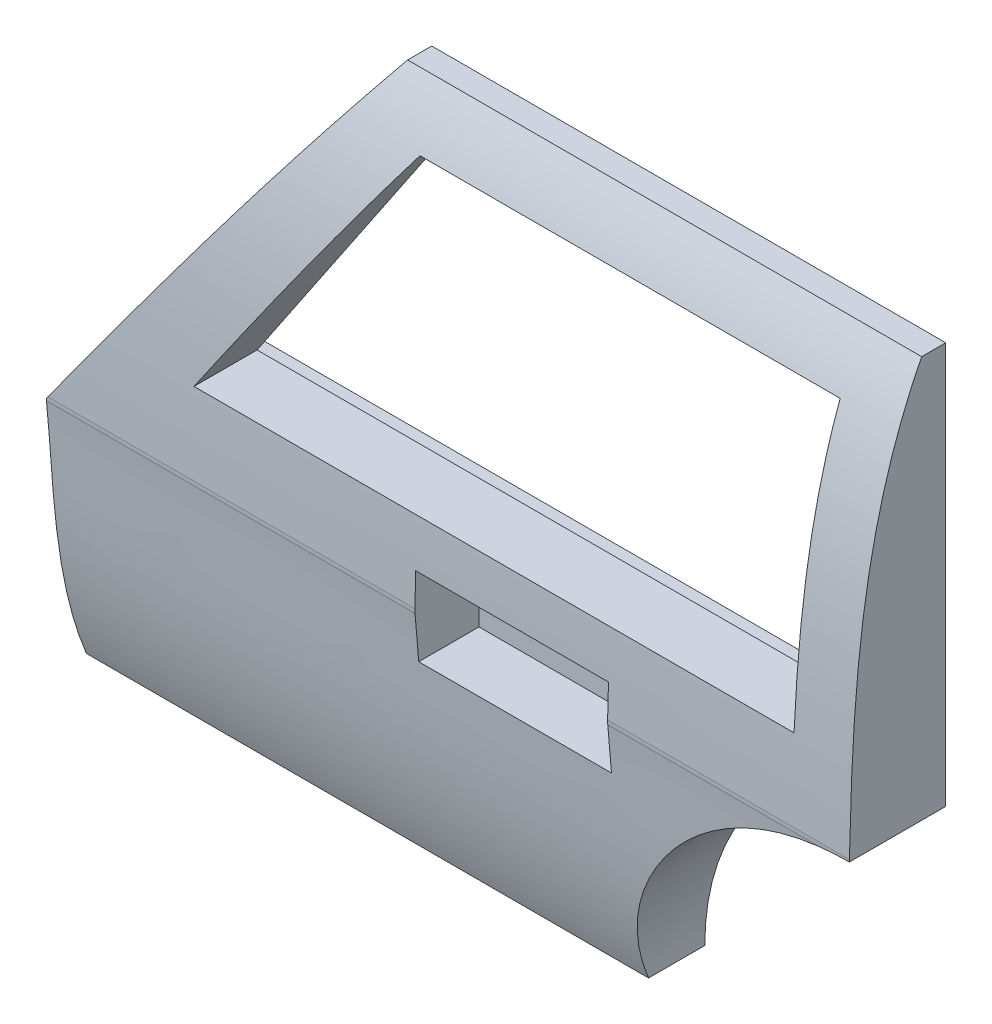
SolidWorks part; units mm, degrees
material "7075-T6, Plate (SS)"
ref_plane "Front Plane" through (0, 0, 0) normal (0, 0, 1) x (1, 0, 0)
ref_plane "Top Plane" through (0, 0, 0) normal (0, 1, 0) x (1, 0, 0)
ref_plane "Right Plane" through (0, 0, 0) normal (1, 0, 0) x (0, 0, -1)
sketch "Sketch1" plane through (0, 0, 0) normal (0, 0, 1) x (1, 0, 0)
  line L0 (0, 0) -> (0, 381)
  line L1 (0, 381) -> (457.2, 1016)
  line L2 (457.2, 1016) -> (1270, 1016)
  line L3 (1270, 1016) -> (1270, 381)
  line L4 (889, 0) -> (0, 0)
  arc A0 (1270, 381) -> (889, 0) centre (1270, 0) ccw
  dimension "D5" = 762
  dimension "D1" = 812.8
  dimension "D2" = 1016
  dimension "D3" = 381
  dimension "D4" = 1270
  dimension "D6" = 635
  dimension "D7" = 889
extrude "Boss-Extrude1" add sketch "Sketch1" along normal mid plane 152.4
sketch "Sketch2" plane through (1270, 0, 0) normal (1, 0, 0) x (0, 0, -1)
  line L0 (-76.2, 1016) -> (38.1, 1016)
  line L1 (-76.2, 1016) -> (76.2, 1016) construction
  line L2 (-76.2, 1016) -> (-76.2, 381)
  spline S0 degree 3 poles (38.1, 1016) (-59.7698, 824.4905) (-71.194, 596.5113) (-76.2, 381) knots 0 0 0 0 1 1 1 1
  dimension "D1" = 114.3
extrude "Cut-Extrude1" cut sketch "Sketch2" against normal through all
sketch "Sketch3" plane through (0, 0, 0) normal (-1, 0, 0) x (0, 0, 1)
  line L0 (76.2, 0) -> (12.7, 0)
  line L1 (76.2, 0) -> (-76.2, 0) construction
  line L2 (76.2, 381) -> (76.2, 0)
  spline S0 degree 3 poles (76.2, 381) (64.471, 274.3699) (67.1703, 132.109) (12.7, 0) knots 0 0 0 0 1 1 1 1
  dimension "D1" = 63.5
extrude "Cut-Extrude2" cut sketch "Sketch3" against normal through all
fillet "Fillet1" radius 50.8 1 edges at (635, 381, 76.2)
sketch "Sketch4" plane through (0, 0, -76.2) normal (0, 0, -1) x (-1, 0, 0)
  line L0 (-1208.6859, 962.0356) -> (-1208.6859, 479.4356)
  line L1 (-1208.6859, 479.4356) -> (-171.9681, 479.4356)
  line L2 (-1208.6859, 962.0356) -> (-497.4859, 962.0356)
  line L3 (-497.4859, 962.0356) -> (-171.9681, 479.4356)
  line L4 (0, 381) -> (0, 0) construction
  line L5 (0, 0) -> (-889, 0) construction
  dimension "D1" = 711.2
  dimension "D2" = 56
  dimension "D3" = 482.6
  dimension "D4" = 1036.7178
  dimension "D5" = 171.9681
  dimension "D6" = 479.4356
extrude "Cut-Extrude3" cut sketch "Sketch4" against normal blind 48.26
sketch3d "3DSketch1"
  line L0 (1178.2059, 931.5556, -27.94) -> (1178.2059, 509.9156, -27.94)
  line L1 (1178.2059, 509.9156, -27.94) -> (229.2926, 509.9156, -27.94)
  line L2 (229.2926, 509.9156, -27.94) -> (513.6924, 931.5556, -27.94)
  line L3 (513.6924, 931.5556, -27.94) -> (1178.2059, 931.5556, -27.94)
  line L4 (1178.2059, 931.5556, -27.94) -> (1178.2059, 509.9156, -27.94)
  line L5 (1178.2059, 509.9156, -27.94) -> (229.2926, 509.9156, -27.94)
  line L6 (229.2926, 509.9156, -27.94) -> (513.6924, 931.5556, -27.94)
  line L7 (513.6924, 931.5556, -27.94) -> (1178.2059, 931.5556, -27.94)
  dimension "D1" = 30.48
extrude "Cut-Extrude4" cut sketch "3DSketch1" along direction (0, 0, -1) on the side of the normal through all
sketch "Sketch5" plane through (-180.6639, 130.078, 0) normal (-0.8115, 0.5843, 0) x (0, 0, 1)
  line L0 (-76.2, 1091.663) -> (-76.2, 309.1946) construction
  line L1 (-76.2, 512.3946) -> (25.4, 512.3946)
  line L2 (-76.2, 512.3946) -> (-76.2, 385.3946)
  line L3 (-76.2, 385.3946) -> (25.4, 385.3946)
  line L4 (25.4, 512.3946) -> (25.4, 385.3946)
  line L5 (76.0904, 309.1946) -> (-76.2, 309.1946) construction
  dimension "D1" = 127
  dimension "D2" = 101.6
  dimension "D3" = 76.2
extrude "Cut-Extrude5" cut sketch "Sketch5" against normal blind 25.4
pattern_linear "LPattern1" count 2 spacing 254 along (0.5843, 0.8115, 0) of "Cut-Extrude5"
ref_plane "Plane1" through (0, 0, 128.3482) normal (0, 0, 1) x (1, 0, 0)
sketch "Sketch6" plane through (0, 0, 128.3482) normal (0, 0, 1) x (1, 0, 0)
  line L1 (582.8613, 435.714) -> (887.6613, 435.714)
  line L2 (582.8613, 435.714) -> (582.8613, 308.714)
  line L3 (582.8613, 308.714) -> (887.6613, 308.714)
  line L4 (887.6613, 435.714) -> (887.6613, 308.714)
  line L5 (582.8613, 435.714) -> (887.6613, 308.714) construction
  line L6 (582.8613, 308.714) -> (887.6613, 435.714) construction
  point P0 (760.6354, 352.0463)
  dimension "D1" = 127
  dimension "D2" = 304.8
extrude "Cut-Extrude6" cut sketch "Sketch6" against normal blind 153.67
